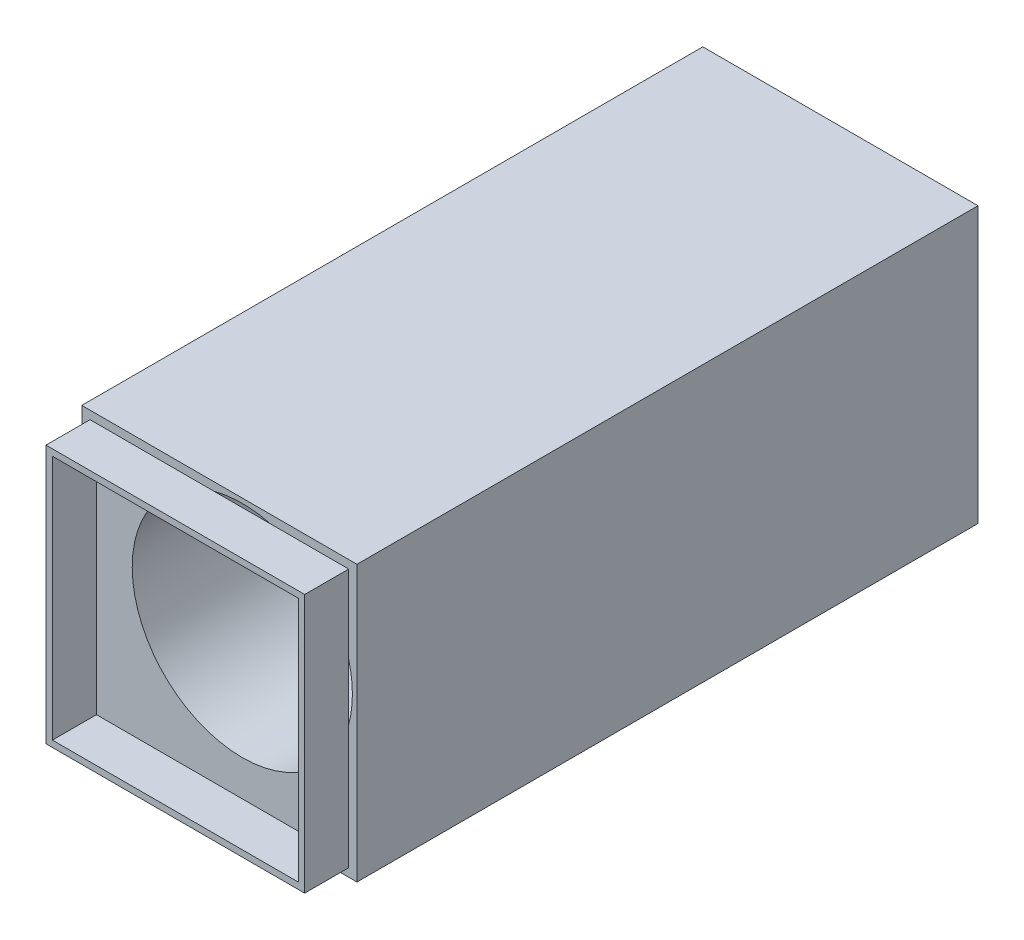
SolidWorks part; units mm, degrees
ref_plane "Front Plane" through (0, 0, 0) normal (0, 0, 1) x (1, 0, 0)
ref_plane "Top Plane" through (0, 0, 0) normal (0, 1, 0) x (1, 0, 0)
ref_plane "Right Plane" through (0, 0, 0) normal (1, 0, 0) x (0, 0, -1)
sketch "Sketch1" plane through (0, 0, 0) normal (0, 0, 1) x (1, 0, 0)
  line L1 (0, 0) -> (76.2, 0)
  line L2 (0, 0) -> (0, 76.2)
  line L3 (0, 76.2) -> (76.2, 76.2)
  line L4 (76.2, 0) -> (76.2, 76.2)
  dimension "D1" = 76.2
  dimension "D2" = 76.2
extrude "Boss-Extrude1" add sketch "Sketch1" against normal blind 184.15
sketch "Sketch3" plane through (0, 0, 0) normal (0, 0, 1) x (1, 0, 0)
  line L0 (0, 76.2) -> (0, 0) construction
  line L1 (2.286, 73.914) -> (73.914, 73.914)
  line L2 (2.286, 73.914) -> (2.286, 2.286)
  line L3 (2.286, 2.286) -> (73.914, 2.286)
  line L4 (73.914, 73.914) -> (73.914, 2.286)
  line L5 (76.2, 0) -> (76.2, 76.2) construction
  line L6 (0, 0) -> (76.2, 0) construction
  line L7 (76.2, 76.2) -> (0, 76.2) construction
  line L9 (4.064, 72.136) -> (72.136, 72.136)
  line L10 (4.064, 72.136) -> (4.064, 4.064)
  line L11 (4.064, 4.064) -> (72.136, 4.064)
  line L12 (72.136, 72.136) -> (72.136, 4.064)
  dimension "D1" = 2.286
  dimension "D2" = 2.286
  dimension "D3" = 2.286
  dimension "D4" = 2.286
  dimension "D5" = 1.778
  dimension "D6" = 1.778
  dimension "D7" = 1.778
  dimension "D8" = 1.778
extrude "Cut-Extrude2" cut sketch "Sketch3" against normal blind 12.192
ref_plane "Plane1" through (0, 0, -107.95) normal (0, 0, -1) x (-1, 0, 0)
sketch "Sketch4" plane through (0, 0, -12.192) normal (0, 0, 1) x (1, 0, 0)
  line L0 (76.2, 76.2) -> (0, 76.2) construction
  line L4 (76.2, 0) -> (76.2, 76.2) construction
  circle A0 centre (44.45, 44.45) radius 30.48
  point P6 (52.07, 25.3994)
  dimension "D1" = 60.96
  dimension "D2" = 31.75
  dimension "D3" = 31.75
extrude "Cut-Extrude4" cut sketch "Sketch4" against normal blind 165.1 contours A0
